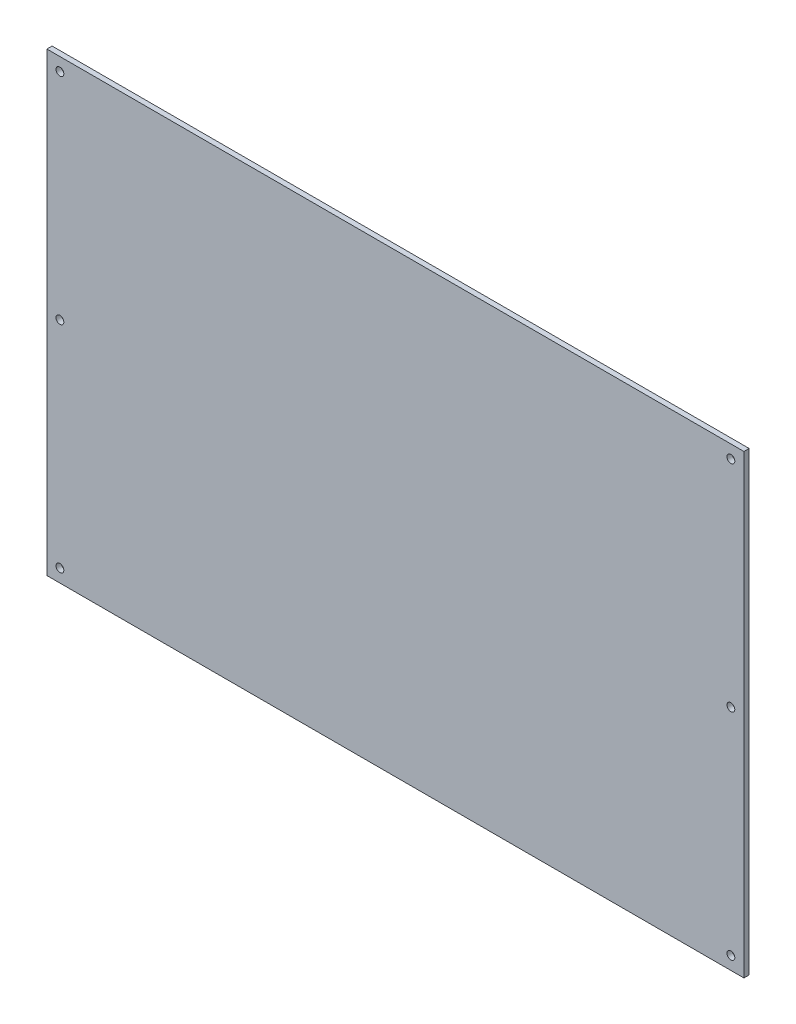
SolidWorks part; units mm, degrees
material "Sklo"
ref_plane "Přední rovina" through (0, 0, 0) normal (0, 0, 1) x (1, 0, 0)
ref_plane "Horní rovina" through (0, 0, 0) normal (0, 1, 0) x (1, 0, 0)
ref_plane "Pravá rovina" through (0, 0, 0) normal (1, 0, 0) x (0, 0, -1)
sketch "Skica1" plane through (0, 0, 0) normal (0, 0, 1) x (1, 0, 0)
  line L1 (267.5, -175) -> (-267.5, -175)
  line L2 (267.5, -175) -> (267.5, 175)
  line L3 (267.5, 175) -> (-267.5, 175)
  line L4 (-267.5, -175) -> (-267.5, 175)
  line L5 (267.5, -175) -> (-267.5, 175) construction
  line L6 (267.5, 175) -> (-267.5, -175) construction
  circle A0 centre (-257.5, 165) radius 3
  circle A1 centre (-257.5, 0) radius 3
  circle A2 centre (-257.5, -165) radius 3
  circle A3 centre (257.5, 165) radius 3
  circle A4 centre (257.5, 0) radius 3
  circle A5 centre (257.5, -165) radius 3
  point P0 (0, 0)
  point P12 (-267.5, 0)
  dimension "D3" = 6
  dimension "D1" = 535
  dimension "D2" = 350
  dimension "D4" = 10
  dimension "D5" = 10
  dimension "D6" = 10
  dimension "D7" = 10
  dimension "D8" = 10
  dimension "D9" = 2
extrude "Přidat vysunutím1" add sketch "Skica1" along normal blind 4
